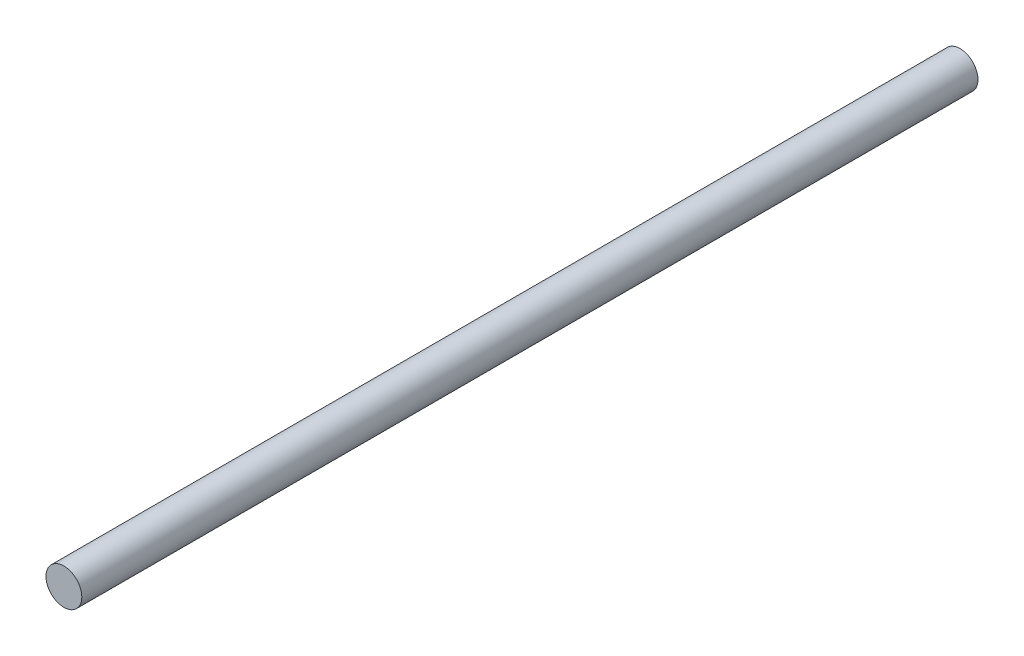
SolidWorks part; units mm, degrees
ref_plane "Alzado" through (0, 0, 0) normal (0, 0, 1) x (1, 0, 0)
ref_plane "Planta" through (0, 0, 0) normal (0, 1, 0) x (1, 0, 0)
ref_plane "Vista lateral" through (0, 0, 0) normal (1, 0, 0) x (0, 0, -1)
sketch "Sketch1" plane through (0, 0, 0) normal (0, 0, 1) x (1, 0, 0)
  circle A0 centre (0, 0) radius 10
  dimension "D1" = 20
extrude "Boss-Extrude1" add sketch "Sketch1" along normal mid plane 500
